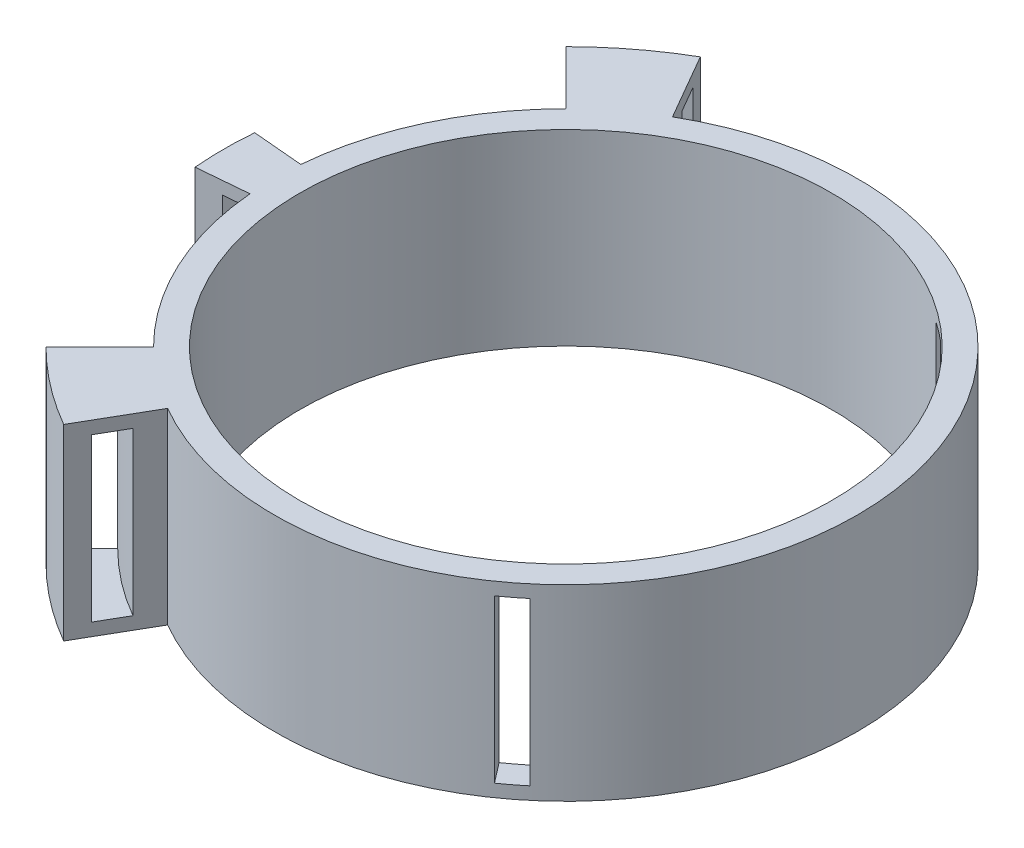
SolidWorks part; units mm, degrees
ref_plane "前视基准面" through (0, 0, 0) normal (0, 0, 1) x (1, 0, 0)
ref_plane "上视基准面" through (0, 0, 0) normal (0, 1, 0) x (1, 0, 0)
ref_plane "右视基准面" through (0, 0, 0) normal (1, 0, 0) x (0, 0, -1)
sketch "草图1" plane through (0, 0, 0) normal (0, 1, 0) x (1, 0, 0)
  line L0 (0, 0) -> (11.4562, -1.0023) construction
  line L1 (0, 0) -> (11.4562, 1.0023) construction
  line L2 (11.4562, 1.0023) -> (10.46, 0.9151)
  line L3 (11.4562, -1.0023) -> (10.46, -0.9151)
  line L5 (0, 0) -> (-5.25, -9.0933) construction
  line L6 (0, 0) -> (-7.4246, -7.4246) construction
  line L7 (0, 0) -> (-5.25, 9.0933) construction
  line L10 (0, 0) -> (-7.4246, 7.4246) construction
  line L11 (-8.1317, 8.1317) -> (-10.253, 10.253)
  line L12 (-5.75, 9.9593) -> (-7.25, 12.5574)
  line L13 (-8.1317, -8.1317) -> (-10.253, -10.253)
  line L14 (-5.75, -9.9593) -> (-7.25, -12.5574)
  line L15 (0, 0) -> (-14.5, 0) construction
  line L16 (0, 0) -> (-10.46, 0.9151) construction
  line L17 (0, 0) -> (-10.46, -0.9151) construction
  line L18 (-11.4562, 1.0023) -> (-13.4486, 1.1766)
  line L19 (-11.4562, -1.0023) -> (-13.4486, -1.1766)
  arc A0 (10.46, 0.9151) -> (10.46, -0.9151) centre (0, 0) ccw
  arc A1 (11.4562, 1.0023) -> (-5.75, 9.9593) centre (0, 0) ccw
  arc A2 (-7.25, 12.5574) -> (-10.253, 10.253) centre (0, 0) ccw
  arc A3 (-10.253, -10.253) -> (-7.25, -12.5574) centre (0, 0) ccw
  arc A4 (-8.1317, 8.1317) -> (-11.4562, 1.0023) centre (0, 0) ccw
  arc A5 (-5.75, -9.9593) -> (11.4562, -1.0023) centre (0, 0) ccw
  arc A6 (-13.4486, 1.1766) -> (-13.4486, -1.1766) centre (0, 0) ccw
  arc A7 (-11.4562, -1.0023) -> (-8.1317, -8.1317) centre (0, 0) ccw
extrude "凸台-拉伸1" add sketch "草图1" along normal blind 0.5
sketch "草图10" plane through (0, 0.5, 0) normal (0, 1, 0) x (1, 0, 0)
  line L0 (0, 0) -> (10.46, -0.9151) construction
  line L1 (10.46, -0.9151) -> (11.4562, -1.0023)
  line L2 (10.46, 0.9151) -> (11.4562, 1.0023)
  line L3 (0, 0) -> (7.3921, -8.8095) construction
  line L4 (7.3921, -8.8095) -> (6.6015, -9.4165) construction
  line L5 (6.6015, -9.4165) -> (5.9919, -8.6225) construction
  line L6 (7.3921, -8.8095) -> (6.7493, -8.0435)
  line L7 (6.6015, -9.4165) -> (5.9919, -8.6225)
  line L8 (0, 0) -> (7.3482, 8.8461) construction
  line L9 (7.3482, 8.8461) -> (6.5537, 9.4498) construction
  line L10 (6.5537, 9.4498) -> (5.9481, 8.6528) construction
  line L11 (5.9481, 8.6528) -> (6.5537, 9.4498)
  line L12 (7.3482, 8.8461) -> (6.7092, 8.0769)
  arc A0 (10.46, 0.9151) -> (6.7092, 8.0769) centre (0, 0) ccw
  arc A1 (11.4562, 1.0023) -> (7.3482, 8.8461) centre (0, 0) ccw
  arc A2 (11.4562, 1.0023) -> (-5.75, 9.9593) centre (0, 0) ccw construction
  arc A3 (6.7493, -8.0435) -> (10.46, -0.9151) centre (0, 0) ccw
  arc A4 (7.3921, -8.8095) -> (11.4562, -1.0023) centre (0, 0) ccw
  arc A5 (5.9481, 8.6528) -> (5.9919, -8.6225) centre (0, 0) ccw
  arc A6 (6.5537, 9.4498) -> (6.6015, -9.4165) centre (0, 0) ccw
  arc M10 (11.4562, 1.0023) -> (-5.75, 9.9593) centre (0, 0) ccw
  line M11 (11.4562, -1.0023) -> (10.46, -0.9151)
  arc M12 (10.46, -0.9151) -> (10.46, 0.9151) centre (0, 0) cw
  line M13 (10.46, 0.9151) -> (11.4562, 1.0023)
extrude "凸台-拉伸2" add sketch "草图10" along normal blind 6.4 contours L6 M10 M11 M12 | L11 L7 M12 M10 | L12 M10 M12 M13
sketch "草图11" plane through (0, 6.9, 0) normal (0, 1, 0) x (1, 0, 0)
  line L0 (11.4562, -1.0023) -> (10.46, -0.9151) construction
  line L1 (10.46, 0.9151) -> (11.4562, 1.0023)
  line L2 (10.46, -0.9151) -> (11.4562, -1.0023)
  arc A0 (10.46, 0.9151) -> (10.46, -0.9151) centre (0, 0) ccw
  arc A1 (11.4562, 1.0023) -> (11.4562, -1.0023) centre (0, 0) ccw
  arc A2 (7.3921, -8.8095) -> (11.4562, -1.0023) centre (0, 0) ccw construction
extrude "凸台-拉伸3" add sketch "草图11" along normal blind 0.5
sketch "草图12" plane through (0, 0.5, 0) normal (0, 1, 0) x (1, 0, 0)
  line L2 (0, 0) -> (-5.4967, 0) construction
  line L3 (-8.1317, -8.1317) -> (-8.8388, -8.8388)
  line L4 (-8.1317, -8.1317) -> (-10.253, -10.253) construction
  line L5 (-5.75, -9.9593) -> (-6.25, -10.8253)
  line L6 (-7.25, -12.5574) -> (-5.75, -9.9593) construction
  line L7 (-10.253, -10.253) -> (-9.6874, -9.6874)
  line L8 (-7.25, -12.5574) -> (-6.85, -11.8645)
  line L9 (-10.253, 10.253) -> (-9.6874, 9.6874)
  line L10 (-7.25, 12.5574) -> (-6.85, 11.8645)
  line L11 (-5.75, 9.9593) -> (-6.25, 10.8253)
  line L12 (-8.1317, 8.1317) -> (-8.8388, 8.8388)
  line L15 (-11.4562, 1.0023) -> (-13.4486, 1.1766) construction
  line L17 (-13.4486, -1.1766) -> (-11.4562, -1.0023) construction
  line L19 (-13.4486, 1.1766) -> (-12.4524, 1.0894)
  line L20 (-13.4486, -1.1766) -> (-12.4524, -1.0894)
  arc A0 (-10.253, -10.253) -> (-7.25, -12.5574) centre (0, 0) ccw
  arc A1 (-8.1317, -8.1317) -> (-5.75, -9.9593) centre (0, 0) ccw
  arc A2 (-8.8388, -8.8388) -> (-6.25, -10.8253) centre (0, 0) ccw
  arc A3 (-9.6874, -9.6874) -> (-6.85, -11.8645) centre (0, 0) ccw
  arc A4 (-10.253, 10.253) -> (-7.25, 12.5574) centre (0, 0) cw
  arc A5 (-9.6874, 9.6874) -> (-6.85, 11.8645) centre (0, 0) cw
  arc A6 (-8.1317, 8.1317) -> (-5.75, 9.9593) centre (0, 0) cw
  arc A7 (-8.8388, 8.8388) -> (-6.25, 10.8253) centre (0, 0) cw
  arc A10 (-12.4524, 1.0894) -> (-12.4524, -1.0894) centre (0, 0) ccw
  arc A12 (-13.4486, -1.1766) -> (-13.4486, 1.1766) centre (0, 0) cw
extrude "凸台-拉伸4" add sketch "草图12" along normal blind 6.4
sketch "草图13" plane through (0, 6.9, 0) normal (0, 1, 0) x (1, 0, 0)
  line L0 (-8.1317, -8.1317) -> (-10.253, -10.253)
  line L1 (-7.25, -12.5574) -> (-5.75, -9.9593)
  line L2 (0, 0) -> (-3.2777, 0) construction
  line L3 (-7.25, 12.5574) -> (-5.75, 9.9593)
  line L4 (-8.1317, 8.1317) -> (-10.253, 10.253)
  line L11 (-13.4486, 1.1766) -> (-11.4562, 1.0023)
  line L12 (-12.4524, 1.0894) -> (-13.4486, 1.1766) construction
  line L13 (-13.4486, -1.1766) -> (-11.4562, -1.0023)
  line L14 (-13.4486, -1.1766) -> (-12.4524, -1.0894) construction
  arc A1 (-7.25, -12.5574) -> (-10.253, -10.253) centre (0, 0) cw
  arc A2 (-5.75, -9.9593) -> (-8.1317, -8.1317) centre (0, 0) cw
  arc A3 (-7.25, 12.5574) -> (-10.253, 10.253) centre (0, 0) ccw
  arc A4 (-5.75, 9.9593) -> (-8.1317, 8.1317) centre (0, 0) ccw
  arc A8 (-13.4486, 1.1766) -> (-13.4486, -1.1766) centre (0, 0) ccw
  arc A9 (-11.4562, 1.0023) -> (-11.4562, -1.0023) centre (0, 0) ccw
extrude "凸台-拉伸5" add sketch "草图13" along normal blind 0.5
sketch "草图14" plane through (0, 7.4, 0) normal (0, 1, 0) x (1, 0, 0)
  line L0 (10.46, 0.9151) -> (11.4562, 1.0023) construction
  line L1 (10.46, 0.9151) -> (11.4562, 1.0023)
  line L2 (10.46, -0.9151) -> (11.4562, -1.0023)
  arc A0 (10.46, -0.9151) -> (10.46, 0.9151) centre (0, 0) ccw
  arc A1 (11.4562, -1.0023) -> (11.4562, 1.0023) centre (0, 0) ccw
extrude "凸台-拉伸6" add sketch "草图14" against normal blind 7.4
